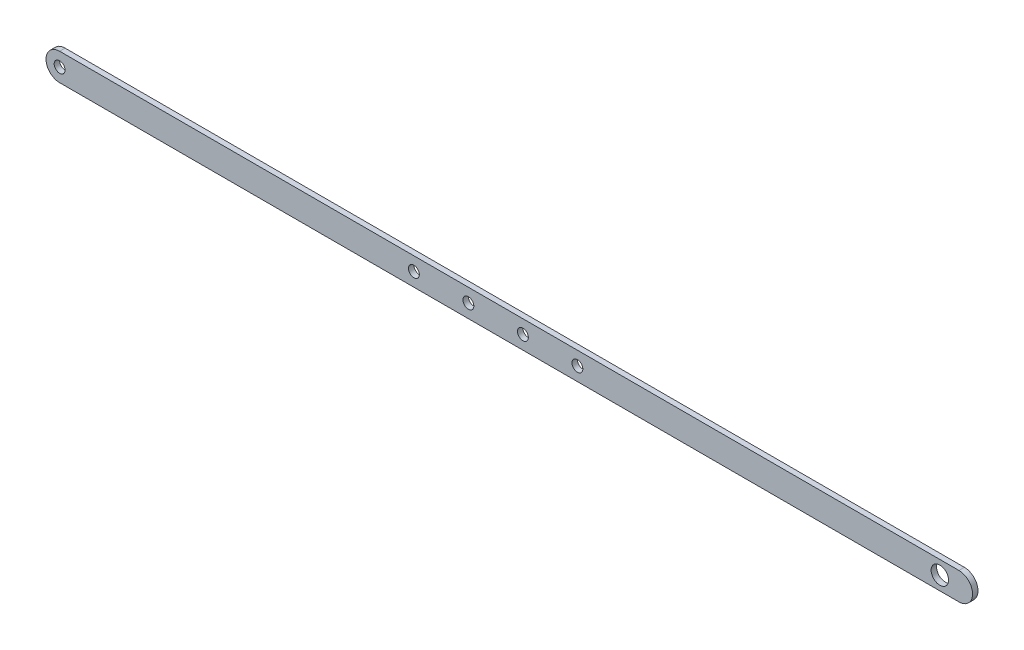
SolidWorks part; units mm, degrees
material "Std CF (1)"
ref_plane "Front Plane" through (0, 0, 0) normal (0, 0, 1) x (1, 0, 0)
ref_plane "Top Plane" through (0, 0, 0) normal (0, 1, 0) x (1, 0, 0)
ref_plane "Right Plane" through (0, 0, 0) normal (1, 0, 0) x (0, 0, -1)
sketch "Sketch1" plane through (0, 0, 0) normal (0, 0, 1) x (1, 0, 0)
  line L0 (0, 0) -> (330, 0) construction
  line L1 (0, 5) -> (330, 5)
  line L2 (0, -5) -> (330, -5)
  arc A0 (0, 5) -> (0, -5) centre (0, 0) ccw
  arc A1 (330, -5) -> (330, 5) centre (330, 0) ccw
  point P3 (165, 0)
  dimension "D1" = 330
  dimension "D2" = 10
extrude "Boss-Extrude1" add sketch "Sketch1" along normal blind 2
sketch "Sketch2" plane through (0, 0, 2) normal (0, 0, 1) x (1, 0, 0)
  circle A0 centre (323, 0) radius 3.2
  arc A1 (330, -5) -> (330, 5) centre (330, 0) ccw construction
  point P5 (335, 0)
  dimension "D1" = 6.4
  dimension "D2" = 12
extrude "Cut-Extrude1" cut sketch "Sketch2" against normal up to surface (2 mm away) up to face at (165, 0, 0)
sketch "Sketch5" plane through (0, 0, 2) normal (0, 0, 1) x (1, 0, 0)
  line L0 (0, -5) -> (330, -5) construction
  circle A0 centre (190, 0) radius 2
  arc A1 (330, -5) -> (330, 5) centre (330, 0) ccw construction
  circle A2 centre (170, 0) radius 2
  circle A3 centre (150, 0) radius 2
  circle A4 centre (130, 0) radius 2
  point P7 (335, 0)
  dimension "D1" = 4
  dimension "D2" = 5
  dimension "D3" = 145
  dimension "D4" = 4
extrude "Cut-Extrude2" cut sketch "Sketch5" against normal up to surface (2 mm away) up to face at (326.2, 0, 0)
sketch "Sketch6" plane through (0, 0, 2) normal (0, 0, 1) x (1, 0, 0)
  circle A0 centre (0, 0) radius 2.5
  dimension "D1" = 5
split line "Split Line1" [suppressed]
sketch "Sketch7" [suppressed] plane through (0, 0, 3) normal (0, 0, 1) x (1, 0, 0)
  circle A0 centre (0, 0) radius 2
  dimension "D1" = 4
extrude "Cut-Extrude3" [suppressed] cut sketch "Sketch7" against normal up to surface (3 mm away)
ref_plane "Plane1" through (0.8551, 0.1508, 0) normal (0.9848, 0.1736, 0) x (0, 0, -1)
sketch "Sketch8" [suppressed] plane through (0.8551, 0.1508, 0) normal (0.9848, 0.1736, 0) x (0, 0, -1)
  line L0 (0, -4.924) -> (0, 5) construction
  line L1 (0, -3.5689) -> (-3, -3.5689)
  line L2 (0, -3.5689) -> (0, 1.7352)
  line L3 (0, 1.7352) -> (-3, 1.7352)
  line L4 (-3, -3.5689) -> (-3, 1.7352)
  line L5 (-3, -4.924) -> (-3, -62.2279) construction
split line "Split Line2" [suppressed]
sketch "Sketch10" plane through (0, 0, 2) normal (0, 0, 1) x (1, 0, 0)
  circle A0 centre (0, 0) radius 2
  dimension "D1" = 4
extrude "Cut-Extrude4" cut sketch "Sketch10" against normal up to surface (2 mm away) up to face at (172, 0, 0)
equation "\"BarWidth\"=10"
equation "\"D2@Sketch5\"=\"D2@Sketch1\"/2"
